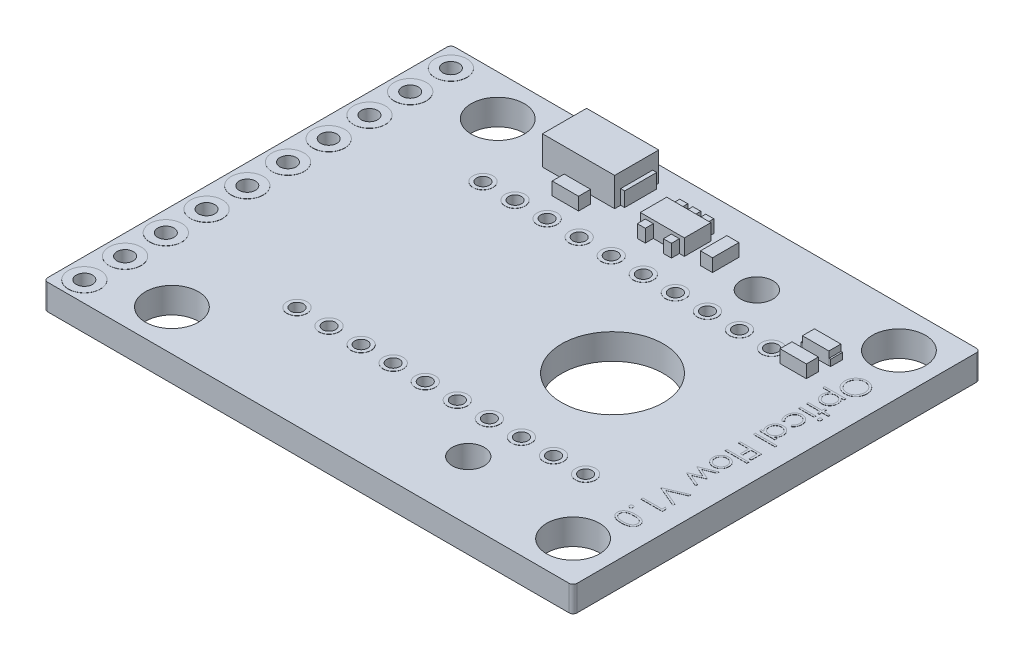
SolidWorks part; units mm, degrees
ref_plane "Front Plane" through (0, 0, 0) normal (0, 0, 1) x (1, 0, 0)
ref_plane "Top Plane" through (0, 0, 0) normal (0, 1, 0) x (1, 0, 0)
ref_plane "Right Plane" through (0, 0, 0) normal (1, 0, 0) x (0, 0, -1)
sketch "Sketch1" plane through (0, 0, 0) normal (0, 1, 0) x (1, 0, 0)
  line L0 (0, 12.7) -> (33.02, 12.7) construction
  line L1 (0, 0) -> (33.02, 0)
  line L2 (0, 0) -> (0, 25.4)
  line L3 (0, 25.4) -> (33.02, 25.4)
  line L4 (33.02, 0) -> (33.02, 25.4)
  circle A0 centre (5.461, 2.54) radius 1.651
  circle A1 centre (30.48, 2.54) radius 1.651
  circle A2 centre (30.48, 22.86) radius 1.651
  circle A3 centre (5.461, 22.86) radius 1.651
  dimension "D3" = 5.461
  dimension "D4" = 2.54
  dimension "D5" = 3.302
  dimension "D6" = 3.302
  dimension "D7" = 30.48
  dimension "D8" = 2.54
  dimension "D1" = 33.02
  dimension "D2" = 25.4
extrude "Boss-Extrude1" add sketch "Sketch1" along normal blind 1.6
sketch "Sketch2" plane through (0, 1.6, 0) normal (0, 1, 0) x (1, 0, 0)
  line L0 (17.78, 17.25) -> (17.78, 8.15) construction
  line L1 (6.505, 17.25) -> (28.805, 17.25) construction
  line L2 (6.505, 17.25) -> (6.505, 8.15) construction
  line L3 (6.505, 8.15) -> (28.805, 8.15) construction
  line L4 (28.805, 17.25) -> (28.805, 8.15) construction
  line L5 (6.505, 12.7) -> (28.805, 12.7) construction
  line L6 (0, 25.4) -> (0, 0) construction
  line L7 (0, 0) -> (33.02, 0) construction
  circle A0 centre (22.78, 12.7) radius 3.175
  circle A1 centre (27.4, 6.4) radius 0.4
  circle A2 centre (25.4, 6.4) radius 0.4
  circle A3 centre (23.4, 6.4) radius 0.4
  circle A4 centre (21.4, 6.4) radius 0.4
  circle A5 centre (19.4, 6.4) radius 0.4
  circle A6 centre (17.4, 6.4) radius 0.4
  circle A7 centre (15.4, 6.4) radius 0.4
  circle A8 centre (13.4, 6.4) radius 0.4
  circle A9 centre (11.4, 6.4) radius 0.4
  circle A10 centre (9.4, 6.4) radius 0.4
  circle A11 centre (26.4, 19) radius 0.4
  circle A12 centre (24.4, 19) radius 0.4
  circle A13 centre (22.4, 19) radius 0.4
  circle A14 centre (20.4, 19) radius 0.4
  circle A15 centre (18.4, 19) radius 0.4
  circle A16 centre (16.4, 19) radius 0.4
  circle A17 centre (14.4, 19) radius 0.4
  circle A18 centre (12.4, 19) radius 0.4
  circle A19 centre (10.4, 19) radius 0.4
  circle A20 centre (8.4, 19) radius 0.4
  circle A21 centre (22.78, 3.7) radius 1
  circle A22 centre (22.78, 21.7) radius 1
  dimension "D5" = 6.35
  dimension "D6" = 5
  dimension "D9" = 9.62
  dimension "D10" = 6.3
  dimension "D11" = 0.8
  dimension "D13" = 0.8
  dimension "D14" = 6.3
  dimension "D15" = 8.62
  dimension "D17" = 9
  dimension "D18" = 5
  dimension "D19" = 2
  dimension "D20" = 2
  dimension "D21" = 9
  dimension "D22" = 5
  dimension "D1" = 22.3
  dimension "D2" = 9.1
  dimension "D3" = 11.275
  dimension "D4" = 11.025
  dimension "D7" = 17.78
  dimension "D8" = 12.7
  dimension "D12" = 10
  dimension "D16" = 10
extrude "Cut-Extrude1" cut sketch "Sketch2" against normal through all
sketch "Sketch3" plane through (0, 1.6, 0) normal (0, 1, 0) x (1, 0, 0)
  line L0 (0, 0) -> (33.02, 0) construction
  line L1 (0, 25.4) -> (0, 0) construction
  circle A0 centre (1.27, 1.27) radius 0.508
  circle A1 centre (1.27, 3.81) radius 0.508
  circle A2 centre (1.27, 6.35) radius 0.508
  circle A3 centre (1.27, 8.89) radius 0.508
  circle A4 centre (1.27, 11.43) radius 0.508
  circle A5 centre (1.27, 13.97) radius 0.508
  circle A6 centre (1.27, 16.51) radius 0.508
  circle A7 centre (1.27, 19.05) radius 0.508
  circle A8 centre (1.27, 21.59) radius 0.508
  circle A9 centre (1.27, 24.13) radius 0.508
  dimension "D1" = 1.27
  dimension "D2" = 1.27
  dimension "D3" = 1.016
  dimension "D4" = 10
extrude "Cut-Extrude2" cut sketch "Sketch3" against normal through all
sketch "Sketch4" plane through (0, 1.6, 0) normal (0, 1, 0) x (1, 0, 0)
  line L0 (33.02, 25.4) -> (0, 25.4) construction
  line L1 (9.461, 24.4) -> (13.961, 24.4)
  line L2 (9.461, 24.4) -> (9.461, 21.65)
  line L3 (9.461, 21.65) -> (13.961, 21.65)
  line L4 (13.961, 24.4) -> (13.961, 21.65)
  circle A0 centre (5.461, 22.86) radius 1.651 construction
  dimension "D1" = 2.75
  dimension "D2" = 4.5
  dimension "D3" = 1
  dimension "D4" = 4
extrude "Boss-Extrude2" add sketch "Sketch4" along normal blind 1.8
sketch "Sketch5" plane through (0, 1.6, 0) normal (0, 1, 0) x (1, 0, 0)
  line L0 (13.961, 21.65) -> (13.961, 24.4) construction
  line L1 (13.961, 24.025) -> (14.211, 24.025)
  line L2 (13.961, 24.025) -> (13.961, 22.025)
  line L3 (13.961, 22.025) -> (14.211, 22.025)
  line L4 (14.211, 24.025) -> (14.211, 22.025)
  line L5 (9.461, 24.4) -> (9.461, 21.65) construction
  line L6 (9.461, 24.025) -> (9.211, 24.025)
  line L7 (9.461, 24.025) -> (9.461, 22.025)
  line L8 (9.461, 22.025) -> (9.211, 22.025)
  line L9 (9.211, 24.025) -> (9.211, 22.025)
  line L11 (13.961, 24.4) -> (9.461, 24.4) construction
  dimension "D1" = 0.25
  dimension "D2" = 2
  dimension "D3" = 2
  dimension "D4" = 0.25
  dimension "D5" = 0.375
  dimension "D6" = 0.375
extrude "Boss-Extrude3" add sketch "Sketch5" along normal blind 0.9
sketch "Sketch6" plane through (0, 1.6, 0) normal (0, 1, 0) x (1, 0, 0)
  line L0 (33.02, 25.4) -> (0, 25.4) construction
  line L1 (15.961, 22.9) -> (18.711, 22.9)
  line L2 (15.961, 22.9) -> (15.961, 21.25)
  line L3 (15.961, 21.25) -> (18.711, 21.25)
  line L4 (18.711, 22.9) -> (18.711, 21.25)
  line L5 (13.961, 24.025) -> (13.961, 22.025) construction
  dimension "D1" = 2.75
  dimension "D2" = 1.65
  dimension "D3" = 2.5
  dimension "D4" = 2
extrude "Boss-Extrude4" add sketch "Sketch6" along normal blind 1
sketch "Sketch7" plane through (0, 1.6, 0) normal (0, 1, 0) x (1, 0, 0)
  line L0 (18.711, 22.9) -> (15.961, 22.9) construction
  line L1 (16.2735, 23.4) -> (16.7735, 23.4)
  line L2 (16.2735, 23.4) -> (16.2735, 22.9)
  line L3 (16.2735, 22.9) -> (16.7735, 22.9)
  line L4 (16.7735, 23.4) -> (16.7735, 22.9)
  line L6 (15.961, 22.9) -> (15.961, 21.25) construction
  line L7 (17.0835, 23.4) -> (17.5835, 23.4)
  line L8 (17.0835, 23.4) -> (17.0835, 22.9)
  line L9 (17.0835, 22.9) -> (17.5835, 22.9)
  line L10 (17.5835, 23.4) -> (17.5835, 22.9)
  line L11 (17.8935, 23.4) -> (18.3935, 23.4)
  line L12 (17.8935, 23.4) -> (17.8935, 22.9)
  line L13 (17.8935, 22.9) -> (18.3935, 22.9)
  line L14 (18.3935, 23.4) -> (18.3935, 22.9)
  line L15 (15.961, 21.25) -> (18.711, 21.25) construction
  line L16 (16.2735, 21.25) -> (16.7735, 21.25)
  line L17 (16.2735, 21.25) -> (16.2735, 20.75)
  line L18 (16.2735, 20.75) -> (16.7735, 20.75)
  line L19 (16.7735, 21.25) -> (16.7735, 20.75)
  line L21 (17.3335, 22.9) -> (17.336, 21.25) construction
  line L22 (17.8985, 21.2517) -> (17.9, 20.7517)
  line L23 (18.4, 20.7532) -> (17.9, 20.7517)
  line L24 (18.3985, 21.2532) -> (18.4, 20.7532)
  line L25 (18.3985, 21.2532) -> (17.8985, 21.2517)
  line L26 (18.711, 21.25) -> (18.711, 22.9) construction
  line L27 (19.711, 22.9) -> (20.461, 22.9)
  line L28 (19.711, 22.9) -> (19.711, 21.2532)
  line L29 (19.711, 21.2532) -> (20.461, 21.2532)
  line L30 (20.461, 22.9) -> (20.461, 21.2532)
  line L31 (9.461, 21.65) -> (13.961, 21.65) construction
  line L32 (11.3142, 21.15) -> (12.961, 21.15)
  line L33 (11.3142, 21.15) -> (11.3142, 20.4)
  line L34 (11.3142, 20.4) -> (12.961, 20.4)
  line L35 (12.961, 21.15) -> (12.961, 20.4)
  line L36 (13.961, 21.65) -> (13.961, 24.4) construction
  line L38 (27.4761, 20.5972) -> (29.1228, 20.5972)
  line L39 (27.4761, 20.5972) -> (27.4761, 19.8472)
  line L40 (27.4761, 19.8472) -> (29.1228, 19.8472)
  line L41 (29.1228, 20.5972) -> (29.1228, 19.8472)
  line L42 (27.4761, 19.1972) -> (29.1228, 19.1972)
  line L43 (27.4761, 19.1972) -> (27.4761, 18.4472)
  line L44 (27.4761, 18.4472) -> (29.1228, 18.4472)
  line L45 (29.1228, 19.1972) -> (29.1228, 18.4472)
  dimension "D1" = 0.5
  dimension "D2" = 0.5
  dimension "D3" = 0.3125
  dimension "D5" = 0.5
  dimension "D6" = 0.5
  dimension "D7" = 0.3125
  dimension "D8" = 1.6468
  dimension "D9" = 0.75
  dimension "D10" = 1
  dimension "D11" = 1.6468
  dimension "D12" = 0.75
  dimension "D13" = 0.5
  dimension "D14" = 1
  dimension "D15" = 0.75
  dimension "D16" = 1.6468
  dimension "D17" = 0.75
  dimension "D18" = 1.6468
  dimension "D19" = 0.65
  dimension "D4" = 3
extrude "Boss-Extrude5" add sketch "Sketch7" along normal blind 0.8
sketch "Sketch9" plane through (0, 1.6, 0) normal (0, 1, 0) x (1, 0, 0)
  circle A0 centre (1.27, 24.13) radius 1
  circle A1 centre (1.27, 24.13) radius 0.508
  circle A2 centre (1.27, 21.59) radius 1
  circle A3 centre (1.27, 21.59) radius 0.508
  circle A4 centre (1.27, 19.05) radius 1
  circle A5 centre (1.27, 19.05) radius 0.508
  circle A6 centre (1.27, 16.51) radius 1
  circle A7 centre (1.27, 16.51) radius 0.508
  circle A8 centre (1.27, 13.97) radius 1
  circle A9 centre (1.27, 13.97) radius 0.508
  circle A10 centre (1.27, 11.43) radius 1
  circle A11 centre (1.27, 11.43) radius 0.508
  circle A12 centre (1.27, 8.89) radius 1
  circle A13 centre (1.27, 8.89) radius 0.508
  circle A14 centre (1.27, 6.35) radius 1
  circle A15 centre (1.27, 6.35) radius 0.508
  circle A16 centre (1.27, 3.81) radius 1
  circle A17 centre (1.27, 3.81) radius 0.508
  circle A18 centre (1.27, 1.27) radius 1
  circle A19 centre (1.27, 1.27) radius 0.508
  circle A20 centre (8.4, 19) radius 0.4
  circle A21 centre (8.4, 19) radius 0.625
  circle A22 centre (10.4, 19) radius 0.4
  circle A23 centre (10.4, 19) radius 0.625
  circle A24 centre (12.4, 19) radius 0.4
  circle A25 centre (12.4, 19) radius 0.625
  circle A26 centre (14.4, 19) radius 0.4
  circle A27 centre (14.4, 19) radius 0.625
  circle A28 centre (16.4, 19) radius 0.4
  circle A29 centre (16.4, 19) radius 0.625
  circle A30 centre (18.4, 19) radius 0.4
  circle A31 centre (18.4, 19) radius 0.625
  circle A32 centre (20.4, 19) radius 0.4
  circle A33 centre (20.4, 19) radius 0.625
  circle A34 centre (22.4, 19) radius 0.4
  circle A35 centre (22.4, 19) radius 0.625
  circle A36 centre (24.4, 19) radius 0.4
  circle A37 centre (24.4, 19) radius 0.625
  circle A38 centre (26.4, 19) radius 0.4
  circle A39 centre (26.4, 19) radius 0.625
  circle A40 centre (9.4, 6.4) radius 0.4
  circle A41 centre (9.4, 6.4) radius 0.625
  circle A42 centre (11.4, 6.4) radius 0.4
  circle A43 centre (11.4, 6.4) radius 0.625
  circle A44 centre (13.4, 6.4) radius 0.4
  circle A45 centre (13.4, 6.4) radius 0.625
  circle A46 centre (15.4, 6.4) radius 0.4
  circle A47 centre (15.4, 6.4) radius 0.625
  circle A48 centre (17.4, 6.4) radius 0.4
  circle A49 centre (17.4, 6.4) radius 0.625
  circle A50 centre (19.4, 6.4) radius 0.4
  circle A51 centre (19.4, 6.4) radius 0.625
  circle A52 centre (21.4, 6.4) radius 0.4
  circle A53 centre (21.4, 6.4) radius 0.625
  circle A54 centre (23.4, 6.4) radius 0.4
  circle A55 centre (23.4, 6.4) radius 0.625
  circle A56 centre (25.4, 6.4) radius 0.4
  circle A57 centre (25.4, 6.4) radius 0.625
  circle A58 centre (27.4, 6.4) radius 0.4
  circle A59 centre (27.4, 6.4) radius 0.625
  dimension "D1" = 2
  dimension "D3" = 1.25
  dimension "D5" = 1.25
  dimension "D2" = 10
  dimension "D4" = 10
  dimension "D6" = 10
extrude "Boss-Extrude6" add sketch "Sketch9" along normal blind 0.01
ref_plane "Plane1" through (0, 0.8, 0) normal (0, 1, 0) x (1, 0, 0)
mirror "Mirror1" about plane through (0, 0.8, 0) normal (0, 1, 0) of "Boss-Extrude6"
fillet "Fillet1" radius 0.25 4 edges at (33.02, 0.8, -25.4) (33.02, 0.8, 0) (0, 0.8, -25.4) (0, 0.8, 0)
sketch "Sketch10" plane through (0, 1.6, 0) normal (0, 1, 0) x (1, 0, 0)
  line L0 (30.48, 22.86) -> (30.48, 2.54) construction
  text T0 "     Optical Flow V1.0" font "Century Gothic" height in points 5
extrude "Boss-Extrude7" add sketch "Sketch10" along normal blind 0.01
sketch "Sketch11" plane through (0, 1.6, 0) normal (0, 1, 0) x (1, 0, 0)
  line L1 (27.4761, 20.5972) -> (27.3761, 20.5972)
  line L2 (27.4761, 20.5972) -> (27.4761, 19.8472)
  line L3 (27.4761, 19.8472) -> (27.3761, 19.8472)
  line L4 (27.3761, 20.5972) -> (27.3761, 19.8472)
  line L5 (29.1228, 20.5972) -> (29.2228, 20.5972)
  line L6 (29.1228, 20.5972) -> (29.1228, 19.8567)
  line L7 (29.1228, 19.8567) -> (29.2228, 19.8567)
  line L8 (29.2228, 20.5972) -> (29.2228, 19.8567)
  dimension "D1" = 0.75
  dimension "D2" = 0.1
  dimension "D3" = 0.1
extrude "Boss-Extrude8" add sketch "Sketch11" along normal blind 0.4 separate body
equation "\"1.3inch\"=75.3367"
